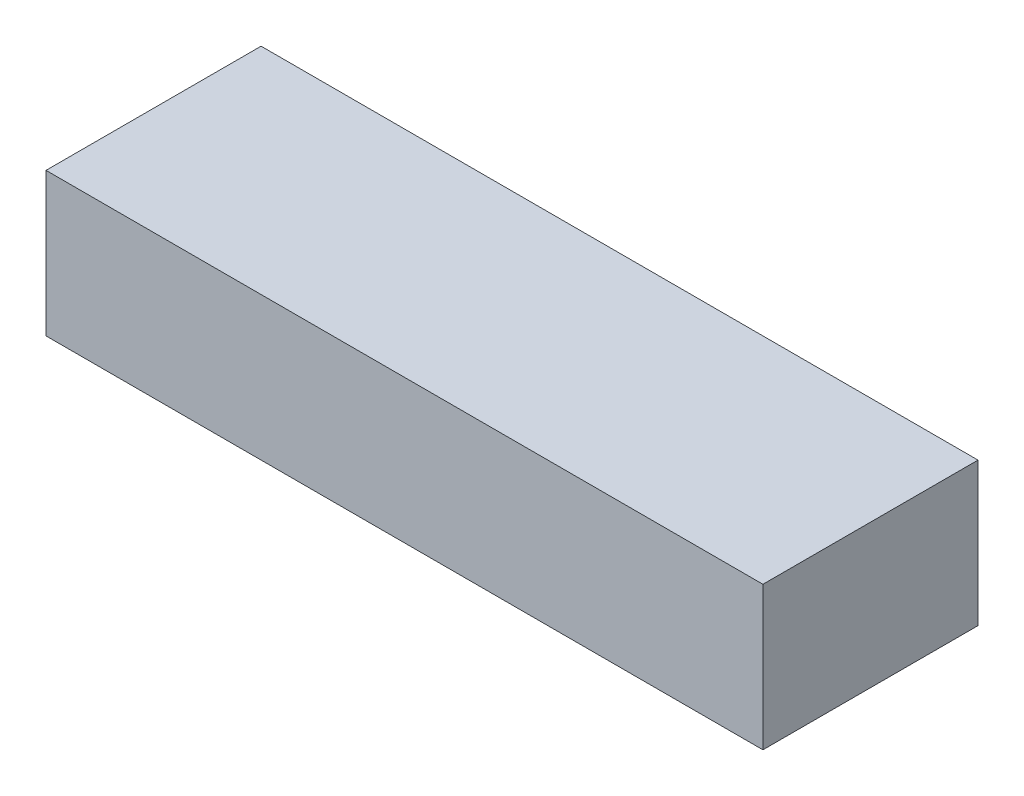
SolidWorks part; units mm, degrees
ref_plane "Plano frontal" through (0, 0, 0) normal (0, 0, 1) x (1, 0, 0)
ref_plane "Plano superior" through (0, 0, 0) normal (0, 1, 0) x (1, 0, 0)
ref_plane "Plano direito" through (0, 0, 0) normal (1, 0, 0) x (0, 0, -1)
sketch "Esboço1" plane through (0, 0, 0) normal (0, 0, 1) x (1, 0, 0)
  line L1 (5, -1) -> (-5, -1)
  line L2 (5, -1) -> (5, 1)
  line L3 (5, 1) -> (-5, 1)
  line L4 (-5, -1) -> (-5, 1)
  line L5 (5, -1) -> (-5, 1) construction
  line L6 (5, 1) -> (-5, -1) construction
  point P0 (0, 0)
  dimension "D1" = 10
  dimension "D2" = 2
extrude "Ressalto-extrusão1" add sketch "Esboço1" along normal blind 3
